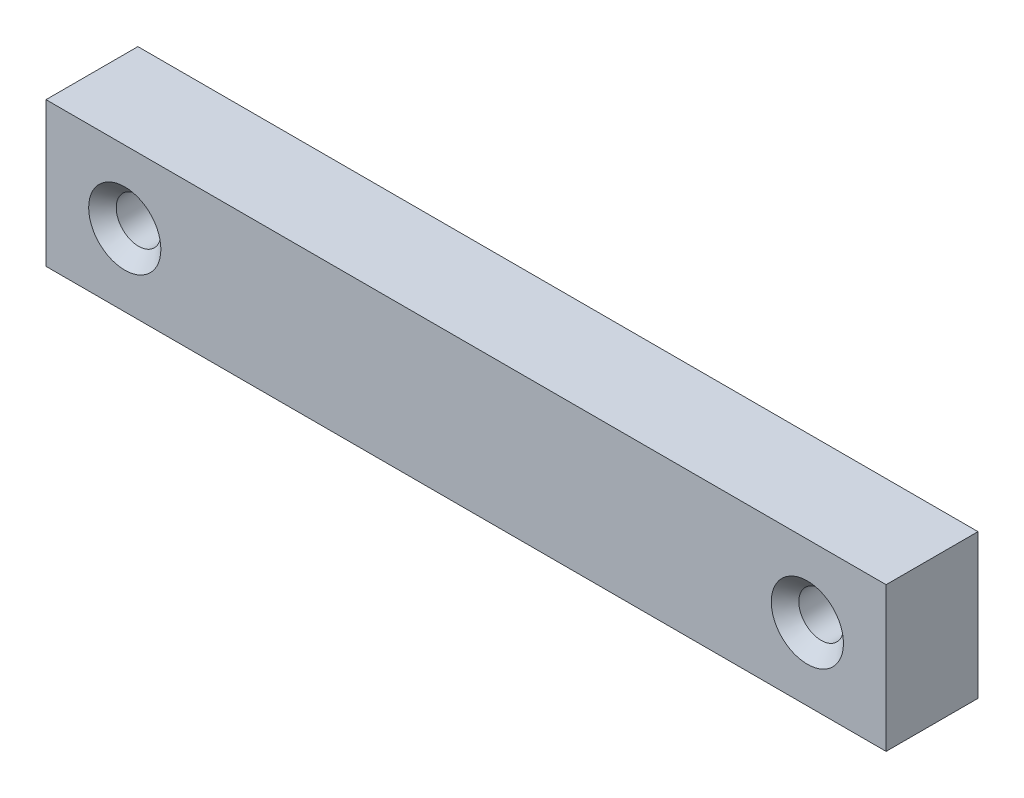
SolidWorks part; units mm, degrees
ref_plane "Front Plane" through (0, 0, 0) normal (0, 0, 1) x (1, 0, 0)
ref_plane "Top Plane" through (0, 0, 0) normal (0, 1, 0) x (1, 0, 0)
ref_plane "Right Plane" through (0, 0, 0) normal (1, 0, 0) x (0, 0, -1)
sketch "Sketch1" plane through (0, 0, 0) normal (0, 0, 1) x (1, 0, 0)
  line L1 (0, 0) -> (64, 0)
  line L2 (0, 0) -> (0, 11)
  line L3 (0, 11) -> (64, 11)
  line L4 (64, 0) -> (64, 11)
  dimension "D1" = 11
  dimension "D2" = 64
extrude "Boss-Extrude1" add sketch "Sketch1" against normal blind 7
sketch "Sketch3" plane through (0, 0, 0) normal (0, 0, 1) x (1, 0, 0)
  line L0 (0, 8.4) -> (64, 8.4) construction
  line L1 (0, 11) -> (0, 0) construction
  line L2 (64, 0) -> (64, 11) construction
  line L3 (0, 5.5) -> (64, 5.5) construction
  circle A0 centre (6, 5.5) radius 2.9 construction
  circle A1 centre (6, 5.5) radius 1.7
  circle A2 centre (58, 5.5) radius 1.7
  point P10 (0, 0)
  point P14 (0, 0)
  dimension "D1" = 5.8
  dimension "D3" = 3.4
  dimension "D4" = 3.4
  dimension "D2" = 6
  dimension "D5" = 52
extrude "Cut-Extrude1" cut sketch "Sketch3" against normal through all
ref_plane "Plane1" through (0, 5.5, 0) normal (0, 1, 0) x (1, 0, 0)
sketch "Sketch6" plane through (0, 0, 0) normal (0, 0, 1) x (1, 0, 0)
  line L0 (6, 11) -> (6, 0)
  line L1 (64, 11) -> (0, 11) construction
  line L2 (0, 0) -> (64, 0) construction
  line L3 (58, 11) -> (58, 0)
  circle A0 centre (58, 5.5) radius 1.7 construction
  circle A1 centre (58, 5.5) radius 1.7
  circle A2 centre (6, 5.5) radius 1.7 construction
  circle A3 centre (6, 5.5) radius 1.7
  point P14 (0, 0)
sketch "Sketch7" plane through (0, 5.5, 0) normal (0, 1, 0) x (1, 0, 0)
  line L0 (6, 0) -> (3.25, 0)
  line L1 (4.3, 0) -> (7.7, 0) construction
  line L2 (0, 0) -> (64, 0) construction
  line L3 (3.25, 0) -> (6, 2.75)
  line L4 (6, 2.75) -> (6, -0.7568) construction
  line L5 (32, 0) -> (32, -17.7476)
  dimension "D1" = 2.75
  dimension "D2" = 3.5068
  dimension "D3" = 45
revolve "Cut-Revolve1" cut sketch "Sketch7" angle 360 about L4
ref_plane "Plane2" through (32, 0, 0) normal (1, 0, 0) x (0, 0, -1)
mirror "Mirror1" about plane through (32, 0, 0) normal (1, 0, 0) of "Cut-Revolve1"
